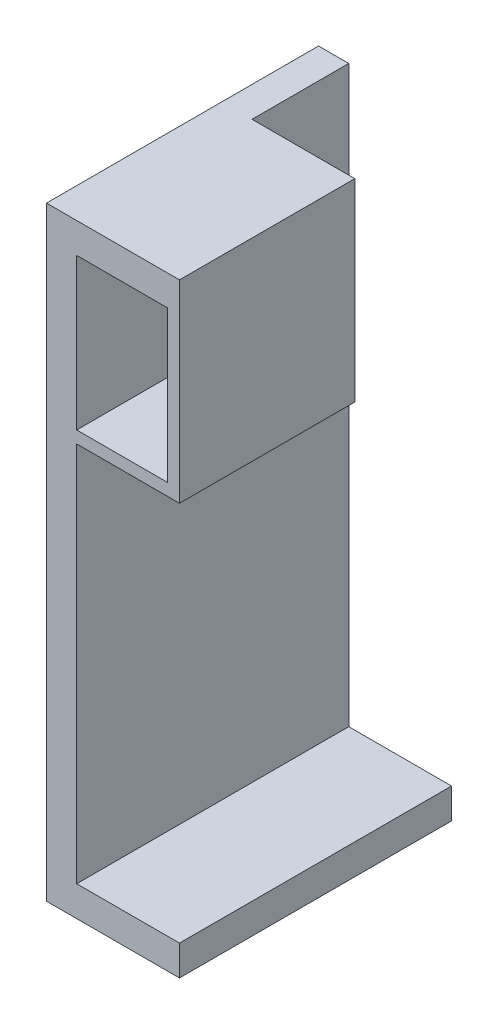
SolidWorks part; units mm, degrees
ref_plane "Front Plane" through (0, 0, 0) normal (1, 0, 0) x (0, 1, 0)
ref_plane "Top Plane" through (0, 0, 0) normal (0, 0, 1) x (0, 1, 0)
ref_plane "Right Plane" through (0, 0, 0) normal (0, 1, 0) x (-1, 0, 0)
sketch "Sketch1" plane through (0, 0, 0) normal (0, 0, 1) x (0, 1, 0)
  line L1 (-50, -37.5) -> (50, -37.5)
  line L2 (-50, -37.5) -> (-50, 37.5)
  line L3 (-50, 37.5) -> (50, 37.5)
  line L4 (50, -37.5) -> (50, 37.5)
  line L5 (-50, -37.5) -> (50, 37.5) construction
  line L6 (-50, 37.5) -> (50, -37.5) construction
  point P0 (0, 0)
extrude "Boss-Extrude1" add sketch "Sketch1" along normal blind 45
sketch "Sketch2" plane through (0, 0, 45) normal (0, 0, 1) x (1, 0, 0)
  line L1 (-32.5, 45) -> (-17.5, 45)
  line L3 (-32.5, 20) -> (-17.5, 20)
  line L4 (-17.5, 45) -> (-17.5, 20)
  line L5 (37.5, 50) -> (-37.5, 50) construction
  line L6 (-32.5, 45) -> (-32.5, 47)
  line L7 (-32.5, 47) -> (-15.5, 47)
  line L8 (-15.5, 47) -> (-15.5, 20)
  line L9 (-15.5, 20) -> (-15.5, 18)
  line L10 (-15.5, 18) -> (-32.5, 18)
  line L11 (-32.5, 18) -> (-32.5, 20)
  line L12 (-32.5, 18) -> (-32.5, -45)
  line L13 (-32.5, -45) -> (32.5, -45)
  line L14 (32.5, -45) -> (32.5, 45)
  line L15 (37.5, -50) -> (37.5, 50) construction
  line L16 (-37.5, -50) -> (37.5, -50) construction
  line L17 (-32.5, 45) -> (-32.5, 20)
  line L18 (32.5, 45) -> (-15.5, 45)
  dimension "D1" = 15
  dimension "D2" = 25
  dimension "D3" = 5
  dimension "D4" = 5
  dimension "D5" = 2
  dimension "D6" = 2
  dimension "D7" = 2
  dimension "D8" = 5
  dimension "D9" = 5
extrude "Cut-Extrude1" cut sketch "Sketch2" against normal through all
sketch "Sketch3" plane through (0, 0, 45) normal (0, 0, 1) x (1, 0, 0)
  line L0 (37.5, 50) -> (-37.5, 50) construction
  line L1 (-15.5, 50) -> (14.6971, 50)
  line L2 (-15.5, 50) -> (-15.5, -50)
  line L3 (-15.5, -50) -> (14.6971, -50)
  line L4 (14.6971, 50) -> (14.6971, -50)
  line L5 (-37.5, -50) -> (37.5, -50) construction
  line L6 (-17.5, 45) -> (-17.5, 20) construction
  point P8 (-15.4663, 50)
  dimension "D1" = 2
extrude "Cut-Extrude2" cut sketch "Sketch3" against normal through all contours L4 L3 L2 L1
sketch "Sketch4" plane through (0, 0, 0) normal (0, 0, 1) x (1, 0, 0)
  line L0 (-15.5, 50) -> (-37.5, 50) construction
  line L1 (-15.5, 18) -> (-32.5, 18)
  line L2 (-15.5, 18) -> (-15.5, 50)
  line L3 (-15.5, 50) -> (-32.5, 50)
  line L4 (-32.5, 18) -> (-32.5, 50)
  line L5 (-37.5, 50) -> (-37.5, -50) construction
  dimension "D1" = 0
  dimension "D2" = 5
extrude "Cut-Extrude3" cut sketch "Sketch4" along normal blind 16
